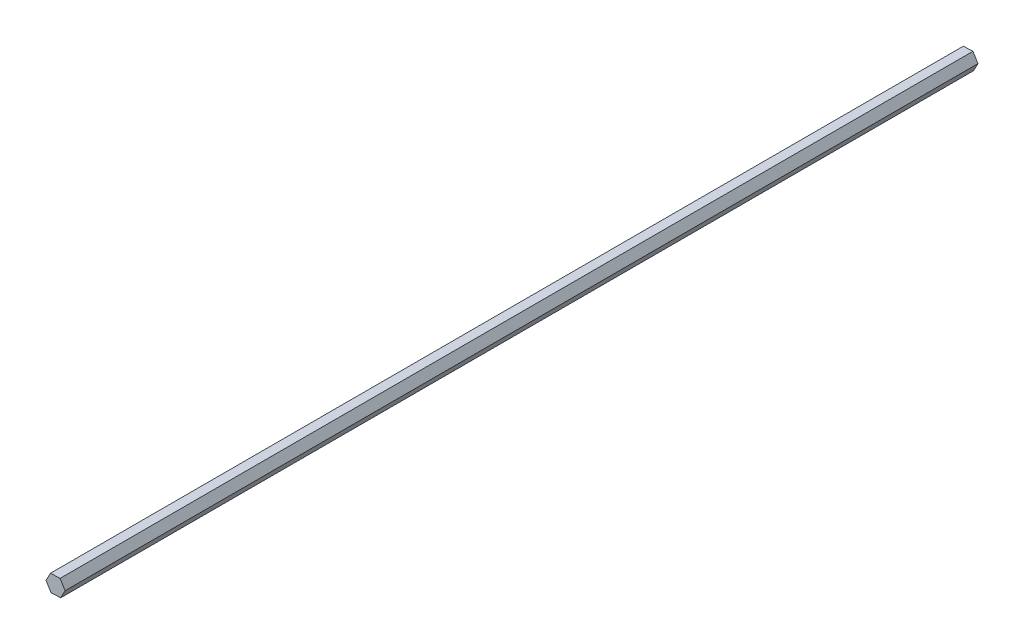
SolidWorks part; units mm, degrees
ref_plane "Front Plane" through (0, 0, 0) normal (0, 0, 1) x (1, 0, 0)
ref_plane "Top Plane" through (0, 0, 0) normal (0, 1, 0) x (1, 0, 0)
ref_plane "Right Plane" through (0, 0, 0) normal (1, 0, 0) x (0, 0, -1)
sketch "Sketch1" plane through (0, 0, 0) normal (0, 0, 1) x (1, 0, 0)
  line L1 (3.8761, -6.2241) -> (7.3283, 0.2447)
  line L2 (7.3283, 0.2447) -> (3.4522, 6.4688)
  line L3 (3.4522, 6.4688) -> (-3.8761, 6.2241)
  line L4 (-3.8761, 6.2241) -> (-7.3283, -0.2447)
  line L5 (-7.3283, -0.2447) -> (-3.4522, -6.4688)
  line L6 (-3.4522, -6.4688) -> (3.8761, -6.2241)
  circle A0 centre (0, 0) radius 6.35 construction
  dimension "D1" = 12.7
extrude "Boss-Extrude1" add sketch "Sketch1" along normal blind 698.5
